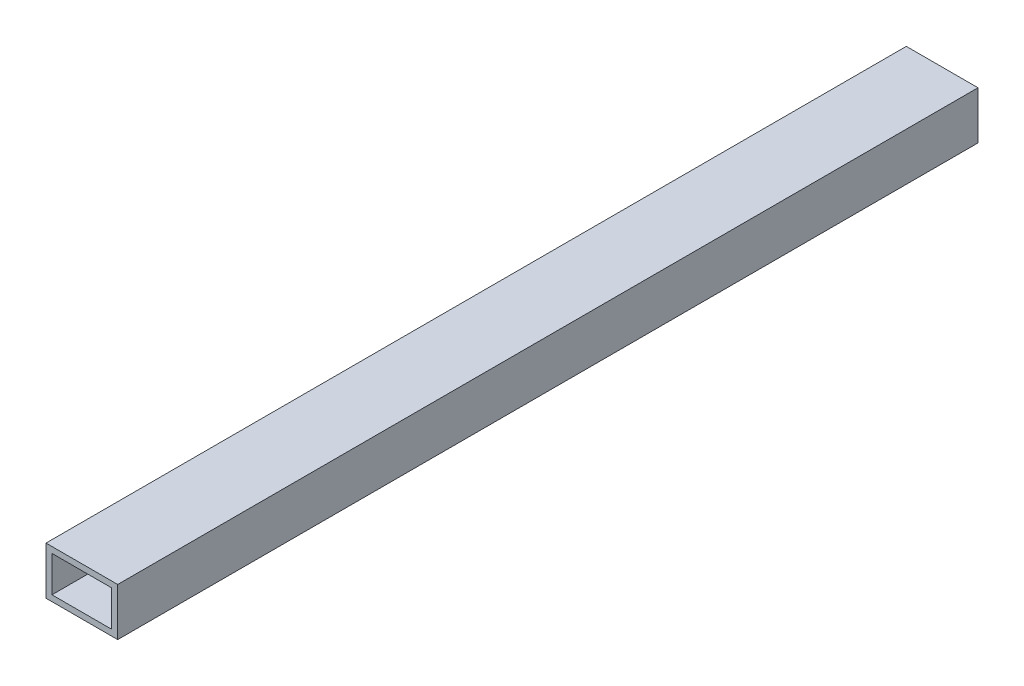
SolidWorks part; units mm, degrees
material "6061 Alloy"
ref_plane "Front Plane" through (0, 0, 0) normal (0, 0, 1) x (1, 0, 0)
ref_plane "Top Plane" through (0, 0, 0) normal (0, 1, 0) x (1, 0, 0)
ref_plane "Right Plane" through (0, 0, 0) normal (1, 0, 0) x (0, 0, -1)
sketch "Sketch1" plane through (0, 0, 0) normal (0, 0, 1) x (1, 0, 0)
  line L0 (19.05, 0) -> (15.875, 0) construction
  line L1 (-19.05, 0) -> (19.05, 0) construction
  line L2 (0, 12.7) -> (0, -12.7)
  point P7 (0, 0)
sketch "Sketch2" plane through (0, 0, 0) normal (1, 0, 0) x (0, 0, -1)
  line L0 (228.6, 0) -> (-228.6, 0)
  point P4 (0, 0)
  dimension "Length" = 457.2
sketch "Sketch3" plane through (0, 0, 0) normal (0, 0, 1) x (1, 0, 0)
  line L0 (-19.05, 0) -> (19.05, 0) construction
  line L5 (19.05, -12.7) -> (-19.05, -12.7)
  line L6 (19.05, -12.7) -> (19.05, 12.7)
  line L11 (19.05, 12.7) -> (-19.05, 12.7)
  line L12 (-19.05, -12.7) -> (-19.05, 12.7)
  line L14 (19.05, -12.7) -> (-19.05, 12.7) construction
  line L15 (19.05, 12.7) -> (-19.05, -12.7) construction
  line L16 (15.875, -9.525) -> (-15.875, -9.525)
  line L17 (15.875, -9.525) -> (15.875, 9.525)
  line L18 (15.875, 9.525) -> (-15.875, 9.525)
  line L19 (-15.875, -9.525) -> (-15.875, 9.525)
  line L20 (15.875, -9.525) -> (-15.875, 9.525) construction
  line L21 (15.875, 9.525) -> (-15.875, -9.525) construction
  point P0 (0, 0)
  point P5 (0, 0)
  point P13 (15.875, -12.7)
  dimension "D1" = 3.175
  dimension "D3" = 38.1
  dimension "D4" = 25.4
  dimension "D2" = 3.175
extrude "Boss-Extrude1" add sketch "Sketch3" along normal up to vertex (228.6 mm away) and the other way up to vertex (228.6 mm away) up to point (0, 0, 228.6) other way up to point (0, 0, -228.6)
sketch "Sketch5" plane through (0, 0, 0) normal (1, 0, 0) x (0, 0, -1)
  line L0 (-228.6, 0) -> (228.6, 0) construction
  line L3 (-228.6, -12.7) -> (-228.6, 12.7) construction
  line L4 (228.6, -12.7) -> (228.6, 12.7) construction
  point P6 (-185.7375, 0)
  point P7 (-171.45, 0)
  point P8 (171.45, 0)
  point P10 (185.7375, 0)
  dimension "D1" = 42.8625
  dimension "D2" = 57.15
  dimension "D3" = 42.8625
  dimension "D4" = 57.15
equation "\"D1@Sketch3\"=\"Wall thickness@Sketch1\""
equation "\"D1@Sketch5\"=\"Width@Sketch1\"*1.125"
equation "\"D2@Sketch5\"=\"Width@Sketch1\"*1.5"
equation "\"D3@Sketch5\"=\"D1@Sketch5\""
equation "\"D4@Sketch5\"=\"D2@Sketch5\""
equation "\"D2@Sketch3\"=\"Wall Thickness@Sketch1\""
